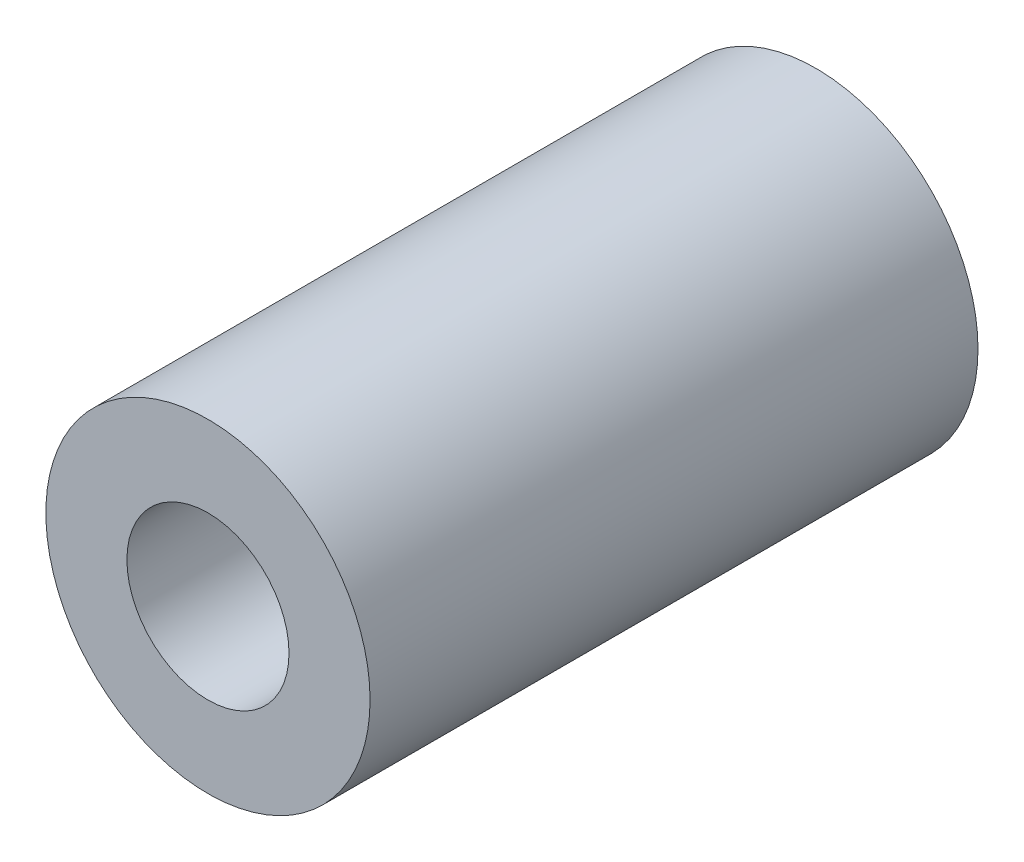
SolidWorks part; units mm, degrees
ref_plane "前基準面" through (0, 0, 0) normal (0, 0, 1) x (1, 0, 0)
ref_plane "上基準面" through (0, 0, 0) normal (0, 1, 0) x (1, 0, 0)
ref_plane "右基準面" through (0, 0, 0) normal (1, 0, 0) x (0, 0, -1)
sketch "草圖1" plane through (0, 0, 0) normal (0, 0, 1) x (1, 0, 0)
  circle A0 centre (0, 0) radius 0.02
  circle A1 centre (0, 0) radius 0.04
extrude "填料-伸長1" add sketch "草圖1" along normal blind 0.15
